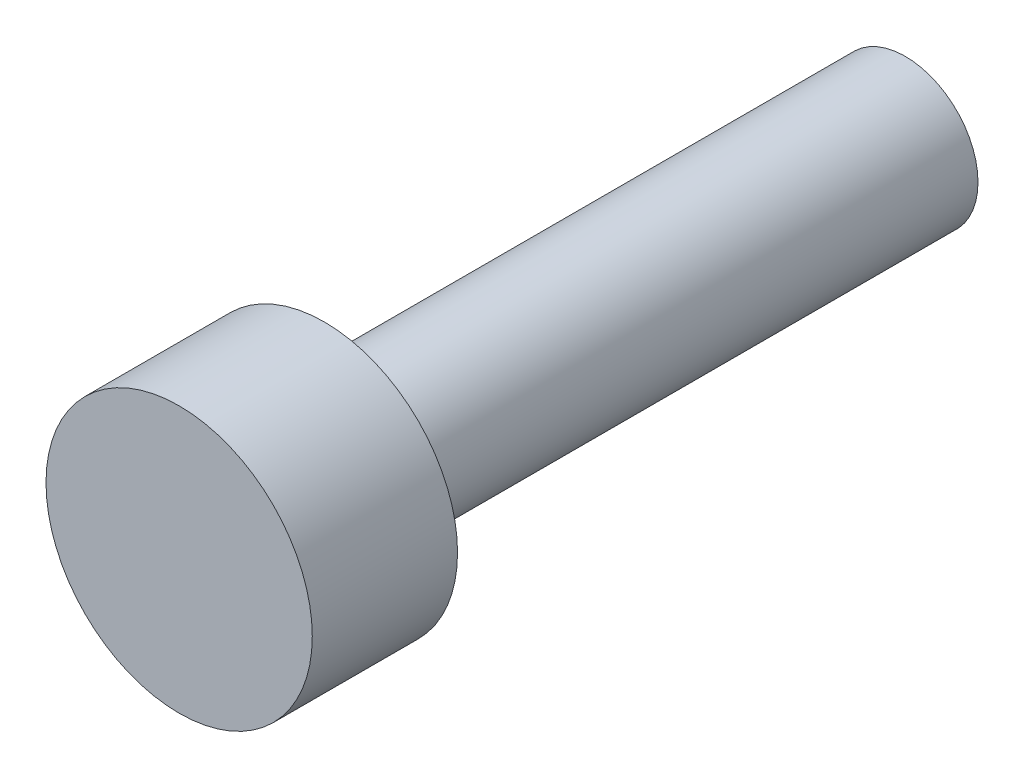
SolidWorks part; units mm, degrees
material "AISI 304"
ref_plane "Front" through (0, 0, 0) normal (0, 0, 1) x (1, 0, 0)
ref_plane "Top" through (0, 0, 0) normal (0, 1, 0) x (1, 0, 0)
ref_plane "Right" through (0, 0, 0) normal (1, 0, 0) x (0, 0, -1)
sketch "Sketch1" plane through (0, 0, 0) normal (0, 0, 1) x (1, 0, 0)
  circle A0 centre (0, 0) radius 1.5
  dimension "D1" = 3
extrude "Boss-Extrude1" add sketch "Sketch1" along normal blind 12
sketch "Sketch2" plane through (0, 0, 12) normal (0, 0, 1) x (1, 0, 0)
  circle A0 centre (0, 0) radius 2.75
  dimension "D1" = 5.5
extrude "Boss-Extrude2" add sketch "Sketch2" along normal blind 3
